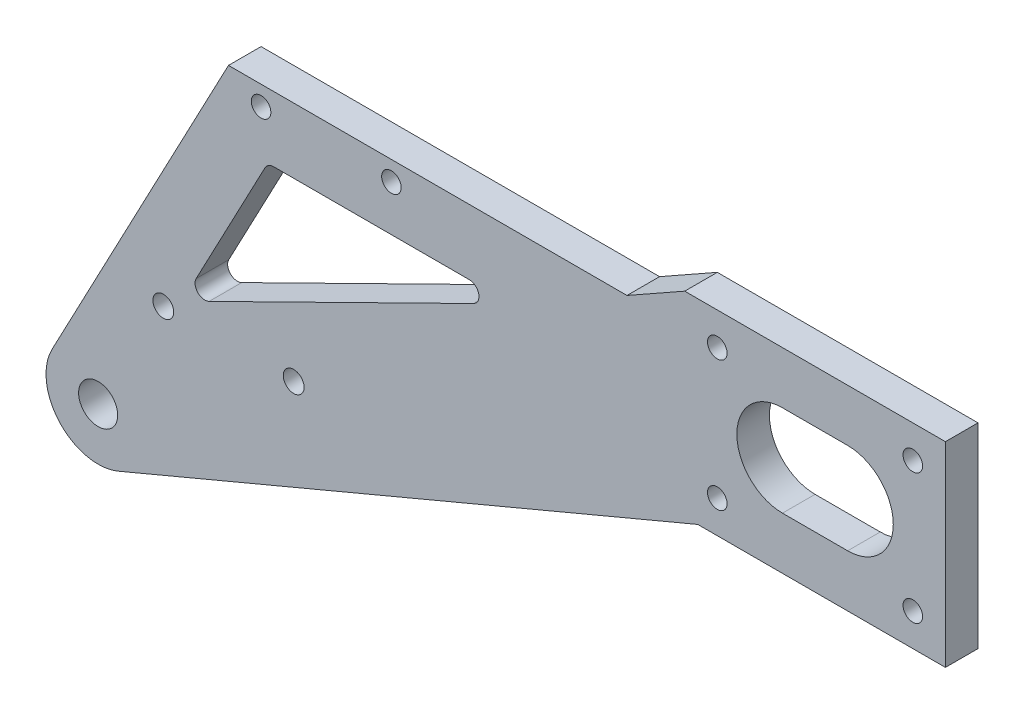
SolidWorks part; units mm, degrees
material "Thornel Mat VMA"
ref_plane "前视基准面" through (0, 0, 0) normal (0, 0, 1) x (1, 0, 0)
ref_plane "上视基准面" through (0, 0, 0) normal (0, 1, 0) x (1, 0, 0)
ref_plane "右视基准面" through (0, 0, 0) normal (1, 0, 0) x (0, 0, -1)
sketch "草图1" plane through (0, 0, 0) normal (0, 0, 1) x (1, 0, 0)
  line L0 (-3.9331, 6.9664) -> (90, 60)
  line L1 (90, 60) -> (130, 60)
  line L2 (130, 60) -> (130, 30)
  line L3 (92, 30) -> (3.1005, -7.3748)
  line L4 (92, 30) -> (130, 30)
  line L5 (125, 55) -> (95, 55) construction
  line L6 (125, 55) -> (125, 35) construction
  line L7 (125, 35) -> (95, 35) construction
  line L8 (95, 55) -> (95, 35) construction
  circle A0 centre (0, 0) radius 3
  arc A1 (-3.9331, 6.9664) -> (3.1005, -7.3748) centre (0, 0) ccw
  circle A2 centre (95, 55) radius 1.5
  circle A3 centre (125, 55) radius 1.5
  circle A4 centre (125, 35) radius 1.5
  circle A5 centre (95, 35) radius 1.5
  dimension "D1" = 6
  dimension "D2" = 40
  dimension "D6" = 8
  dimension "D7" = 5
  dimension "D11" = 3
  dimension "D3" = 30
  dimension "D4" = 60
  dimension "D5" = 90
  dimension "D8" = 5
  dimension "D9" = 5
  dimension "D10" = 5
  dimension "D12" = 3
extrude "凸台-拉伸1" add sketch "草图1" along normal blind 5
sketch "草图3" plane through (0, 0, 5) normal (0, 0, 1) x (1, 0, 0)
  line L0 (81.144, 55) -> (20, 55)
  line L1 (90, 60) -> (-3.9331, 6.9664) construction
  line L2 (20, 55) -> (20, 20.4788)
  line L3 (20, 20.4788) -> (81.144, 55)
  line L4 (92, 30) -> (130, 30) construction
  circle A0 centre (95, 55) radius 1.5 construction
  dimension "D1" = 25
  dimension "D2" = 75
extrude "凸台-拉伸2" add sketch "草图3" against normal up to surface (5 mm away) up to face at (72.4002, 29.3788, 0)
sketch "草图4" plane through (0, 0, 5) normal (0, 0, 1) x (1, 0, 0)
  line L0 (25, 52) -> (45, 52) construction
  line L1 (81.144, 55) -> (20, 55) construction
  circle A0 centre (25, 52) radius 1.5
  circle A1 centre (45, 52) radius 1.5
  circle A2 centre (95, 55) radius 1.5 construction
  dimension "D1" = 3
  dimension "D4" = 3
  dimension "D2" = 20
  dimension "D3" = 50
extrude "切除-拉伸1" cut sketch "草图4" against normal through all
sketch "草图6" plane through (0, 0, 5) normal (0, 0, 1) x (1, 0, 0)
  line L0 (-7.074, 3.736) -> (20, 55)
  line L1 (20, 55) -> (20, 20.4788) construction
  line L2 (20, 20.4788) -> (-3.9331, 6.9664) construction
  line L3 (20, 55) -> (20, 20.4788)
  line L4 (20, 20.4788) -> (-3.9331, 6.9664)
  arc A0 (-3.9331, 6.9664) -> (3.1005, -7.3748) centre (0, 0) ccw construction
  arc A1 (-3.9331, 6.9664) -> (-7.074, 3.736) centre (0, 0) ccw
extrude "凸台-拉伸3" add sketch "草图6" against normal up to surface (5 mm away) up to face at (26.5, 52, 0)
sketch "草图5" plane through (0, 0, 5) normal (0, 0, 1) x (1, 0, 0)
  line L3 (20, 55) -> (-7.074, 3.736) construction
  line L10 (81.144, 55) -> (20, 55) construction
  line L11 (105, 45) -> (115, 45) construction
  line L12 (95, 55) -> (125, 55) construction
  line L13 (95, 55) -> (95, 35) construction
  line L14 (95, 35) -> (125, 35) construction
  line L15 (125, 55) -> (125, 35) construction
  line L16 (105, 52) -> (115, 52)
  line L17 (105, 38) -> (115, 38)
  line L21 (25.6054, 44.2005) -> (15.0428, 24.2005)
  line L22 (17.0325, 22.1546) -> (57.5951, 42.1546)
  line L24 (56.9318, 45) -> (26.9318, 45)
  arc A11 (105, 52) -> (105, 38) centre (105, 45) ccw
  arc A12 (115, 38) -> (115, 52) centre (115, 45) ccw
  arc A13 (57.5951, 42.1546) -> (56.9318, 45) centre (56.9318, 43.5) ccw
  arc A14 (15.0428, 24.2005) -> (17.0325, 22.1546) centre (16.3692, 23.5) ccw
  arc A15 (25.6054, 44.2005) -> (26.9318, 45) centre (26.9318, 43.5) cw
  point P15 (0, 0)
  point P29 (110, 45)
  point P30 (110, 55)
  point P53 (95, 45)
  dimension "D3" = 10
  dimension "D10" = 7
  dimension "D4" = 1.5
  dimension "D8" = 30
  dimension "D2" = 10
  dimension "D11" = 10
  dimension "D12" = 20
extrude "切除-拉伸2" cut sketch "草图5" against normal through all
sketch "草图7" plane through (0, 0, 5) normal (0, 0, 1) x (1, 0, 0)
  line L0 (10, 18) -> (30, 18) construction
  circle A0 centre (10, 18) radius 1.6
  circle A1 centre (30, 18) radius 1.6
  dimension "D2" = 3.2
  dimension "D1" = 20
  dimension "D3" = 10
  dimension "D4" = 18
extrude "切除-拉伸3" cut sketch "草图7" against normal through all
